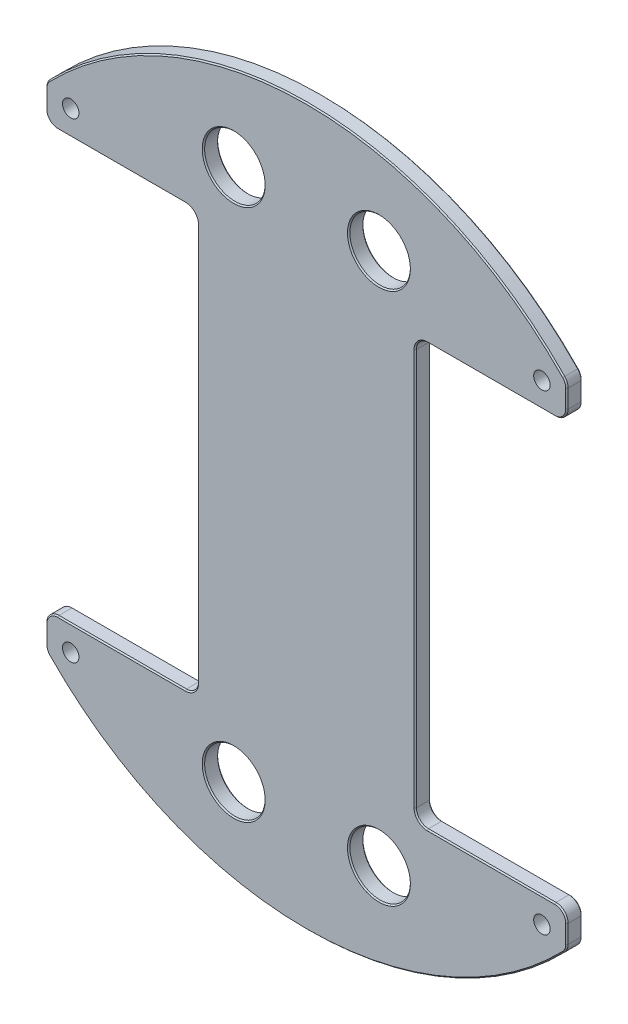
SolidWorks part; units mm, degrees
material "Copper"
ref_plane "Front Plane" through (0, 0, 0) normal (0, 0, 1) x (1, 0, 0)
ref_plane "Top Plane" through (0, 0, 0) normal (0, 1, 0) x (1, 0, 0)
ref_plane "Right Plane" through (0, 0, 0) normal (1, 0, 0) x (0, 0, -1)
sketch "Sketch1" plane through (0, 0, 0) normal (0, 0, 1) x (1, 0, 0)
  line L3 (0, -55) -> (0, 55) construction
  line L7 (-48.6666, 48.6666) -> (48.6666, -48.6666) construction
  line L8 (55, 0) -> (-55, 0) construction
  line L9 (-53.8416, 50.7649) -> (-53.8416, 43.4916)
  line L10 (-53.8416, 43.4916) -> (-22.5, 43.4916)
  line L11 (-22.5, 43.4916) -> (-22.5, -43.4916)
  line L12 (22.5, 43.4916) -> (22.5, -43.4916)
  line L14 (53.8416, 43.4916) -> (22.5, 43.4916)
  line L15 (53.8416, 50.7649) -> (53.8416, 43.4916)
  line L17 (-53.8416, -43.4916) -> (-22.5, -43.4916)
  line L18 (-53.8416, -50.7649) -> (-53.8416, -43.4916)
  line L19 (53.8416, -50.7649) -> (53.8416, -43.4916)
  line L20 (53.8416, -43.4916) -> (22.5, -43.4916)
  line L22 (48.6666, 48.6666) -> (-48.6666, -48.6666) construction
  arc A0 (53.8416, 50.7649) -> (-53.8416, 50.7649) centre (0, 0) ccw
  arc A2 (53.8416, -50.7649) -> (-53.8416, -50.7649) centre (0, 0) cw
  circle A3 centre (-48.6666, 48.6666) radius 5.175 construction
  point P18 (0, 0)
  point P19 (-22.5, 0)
  point P27 (22.5, 0)
  dimension "D1" = 148
  dimension "D2" = 45
  dimension "D3" = 137.65
  dimension "D4" = 45
extrude "Boss-Extrude1" add sketch "Sketch1" along normal blind 3.175
hole_wizard "M3 Clearance Hole1" positions "3DSketch3" profile "Sketch3" hole size "M3" standard "ANSI Metric" end condition through all
sketch3d "3DSketch3"
  point P0 (48.6666, 48.6666, 0)
  point P2 (-48.6666, 48.6666, 0)
  point P4 (-48.6666, -48.6666, 0)
  point P6 (48.6666, -48.6666, 0)
sketch "Sketch3" plane through (48.6666, 48.6666, 0) normal (1, 0, 0) x (0, 1, 0)
  line L0 (0, 0) -> (0, 3.175)
  line L1 (0, 3.175) -> (1.7, 3.175)
  line L2 (1.7, 3.175) -> (1.7, 0)
  line L5 (1.7, 0) -> (0, 0)
  line L11 (0, -6.35) -> (0, 107.95) construction
  dimension "Thru Hole Dia." = 3.4
  dimension "Thru Hole Depth" = 3.175
sketch "Sketch7" plane through (0, 0, 0) normal (0, 0, -1) x (-1, 0, 0)
  line L0 (0, 1.7463) -> (0, -1.7463) construction
  line L1 (1.7463, 0) -> (-1.7463, 0) construction
  circle A0 centre (15, 55) radius 6.25
  circle A1 centre (-15, 55) radius 6.25
  circle A2 centre (-15, -55) radius 6.25
  circle A3 centre (15, -55) radius 6.25
  point P12 (14.0368, 59.0095)
  dimension "D1" = 12.5
  dimension "D2" = 30
  dimension "D3" = 55
extrude "Cut-Extrude3" cut sketch "Sketch7" against normal through all
fillet "Fillet1" radius 2.5 12 edges at (53.8416, 50.7649, 1.5875) (53.8416, 43.4916, 1.5875) (53.8416, -43.4916, 1.5875) (53.8416, -50.7649, 1.5875) (-53.8416, -43.4916, 1.5875) (-53.8416, 43.4916, 1.5875) (-53.8416, 50.7649, 1.5875) (-53.8416, -50.7649, 1.5875) (22.5, 43.4916, 1.5875) (22.5, -43.4916, 1.5875) (-22.5, -43.4916, 1.5875) (-22.5, 43.4916, 1.5875)
chamfer "Chamfer1" distance 0.25 angle 45 56 edges at (-21.25, 55, 0) (-21.25, 55, 3.175) (21.25, 55, 0) (21.25, 55, 3.175) (8.75, -55, 0) (8.75, -55, 3.175) (-8.75, -55, 0) (-8.75, -55, 3.175) (22.5, 0, 3.175) (23.2322, 42.7594, 3.175) (23.2322, -42.7594, 3.175) (38.1708, 43.4916, 3.175) (38.1708, -43.4916, 3.175) (53.1094, 44.2239, 3.175) (53.1094, -44.2239, 3.175) (53.8416, 47.877, 3.175) (53.8416, -47.877, 3.175) (53.6587, 50.701, 3.175) (53.6587, -50.701, 3.175) (0, 74, 3.175) (0, -74, 3.175) (-53.6587, 50.701, 3.175) (-53.6587, -50.701, 3.175) (-53.8416, 47.877, 3.175) (-53.8416, -47.877, 3.175) (-53.1094, 44.2239, 3.175) (-53.1094, -44.2239, 3.175) (-38.1708, 43.4916, 3.175) (-38.1708, -43.4916, 3.175) (-23.2322, 42.7594, 3.175) (-23.2322, -42.7594, 3.175) (-22.5, 0, 3.175) (22.5, 0, 0) (23.2322, 42.7594, 0) (23.2322, -42.7594, 0) (38.1708, 43.4916, 0) (38.1708, -43.4916, 0) (53.1094, 44.2239, 0) (53.1094, -44.2239, 0) (53.8416, 47.877, 0) (53.8416, -47.877, 0) (53.6587, 50.701, 0) (53.6587, -50.701, 0) (0, 74, 0) (0, -74, 0) (-53.6587, 50.701, 0) (-53.6587, -50.701, 0) (-53.8416, 47.877, 0) (-53.8416, -47.877, 0) (-53.1094, 44.2239, 0) (-53.1094, -44.2239, 0) (-38.1708, 43.4916, 0) (-38.1708, -43.4916, 0) (-23.2322, 42.7594, 0) (-23.2322, -42.7594, 0) (-22.5, 0, 0)
